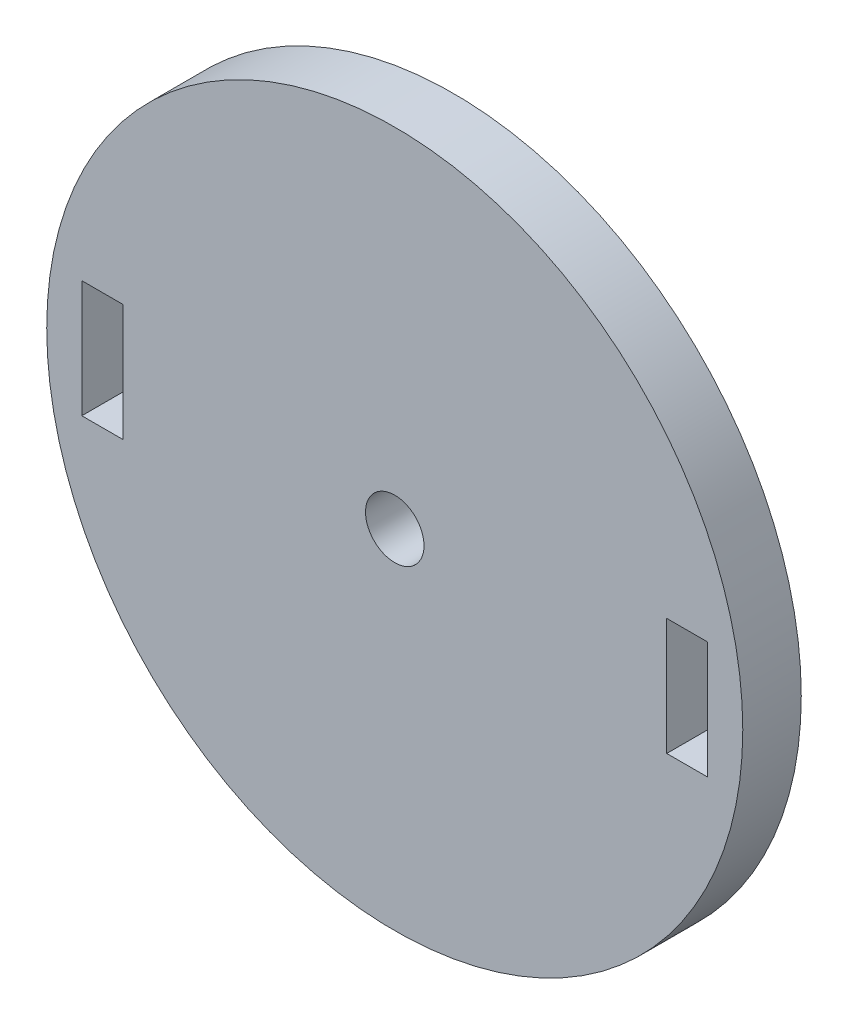
SolidWorks part; units mm, degrees
ref_plane "Front Plane" through (0, 0, 0) normal (0, 0, 1) x (1, 0, 0)
ref_plane "Top Plane" through (0, 0, 0) normal (0, 1, 0) x (1, 0, 0)
ref_plane "Right Plane" through (0, 0, 0) normal (1, 0, 0) x (0, 0, -1)
sketch "Sketch1" plane through (0, 0, 0) normal (0, 0, 1) x (1, 0, 0)
  line L0 (-9.5372, 1.6245) -> (10.4628, 1.6245) construction
  line L1 (0.4628, 1.6245) -> (0.4628, 7.6258) construction
  line L2 (11.1628, 3.6245) -> (9.7628, 3.6245)
  line L3 (11.1628, 3.6245) -> (11.1628, -0.3755)
  line L4 (11.1628, -0.3755) -> (9.7628, -0.3755)
  line L5 (9.7628, 3.6245) -> (9.7628, -0.3755)
  line L6 (11.1628, 3.6245) -> (9.7628, -0.3755) construction
  line L7 (11.1628, -0.3755) -> (9.7628, 3.6245) construction
  line L8 (-10.2372, -0.3755) -> (-8.8372, 3.6245) construction
  line L9 (-10.2372, 3.6245) -> (-8.8372, -0.3755) construction
  line L10 (-8.8372, 3.6245) -> (-8.8372, -0.3755)
  line L11 (-10.2372, -0.3755) -> (-8.8372, -0.3755)
  line L12 (-10.2372, 3.6245) -> (-10.2372, -0.3755)
  line L13 (-10.2372, 3.6245) -> (-8.8372, 3.6245)
  circle A0 centre (0.4628, 1.6245) radius 11.9
  circle A1 centre (0.4628, 1.6245) radius 1
  dimension "D1" = 23.8
  dimension "D2" = 2
  dimension "D3" = 10
  dimension "D4" = 4
  dimension "D5" = 1.4
extrude "Boss-Extrude1" add sketch "Sketch1" along normal blind 2
